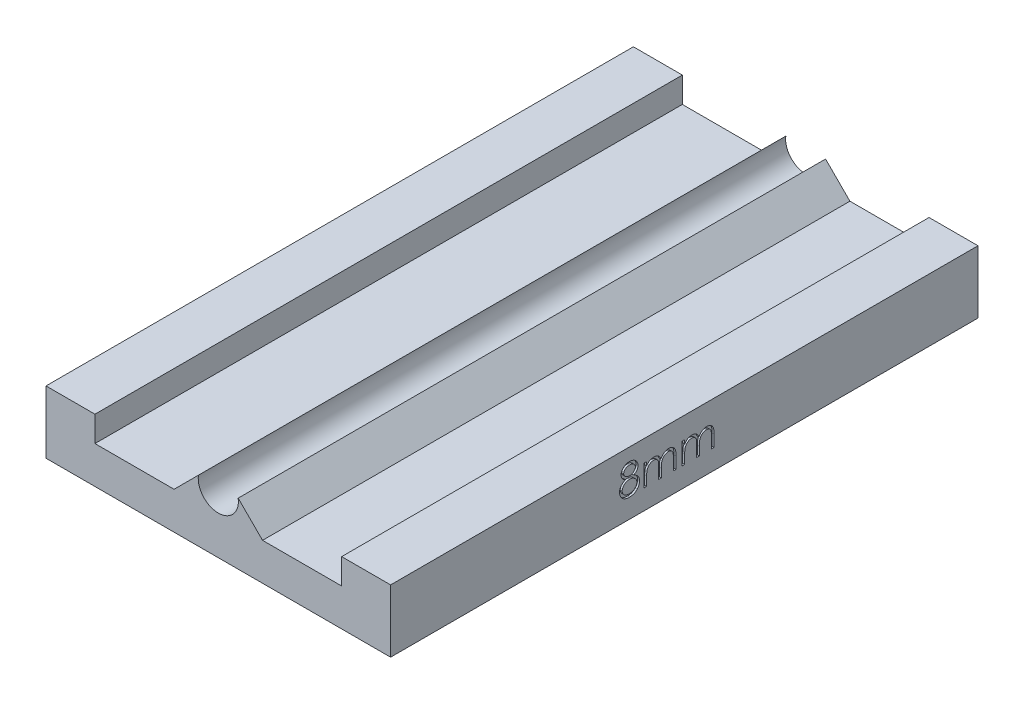
SolidWorks part; units mm, degrees
ref_plane "Front Plane" through (0, 0, 0) normal (0, 0, 1) x (1, 0, 0)
ref_plane "Top Plane" through (0, 0, 0) normal (0, 1, 0) x (1, 0, 0)
ref_plane "Right Plane" through (0, 0, 0) normal (1, 0, 0) x (0, 0, -1)
sketch "Sketch1" plane through (0, 0, 0) normal (0, 0, 1) x (1, 0, 0)
  line L0 (0, 0) -> (0, 5.7983) construction
  line L1 (0, 5.7983) -> (-10, -4.2017)
  line L2 (0, 5.7983) -> (10, -4.2017)
  line L3 (-10, -4.2017) -> (-25, -4.2017)
  line L4 (-25, -4.2017) -> (-25, 15.7983)
  line L5 (-25, 15.7983) -> (25, 15.7983)
  line L6 (25, 15.7983) -> (25, -4.2017)
  line L7 (25, -4.2017) -> (10, -4.2017)
  line L8 (-35.2, 0.7983) -> (-35.2, -12)
  line L9 (-35.2, -12) -> (35.2, -12)
  line L10 (35.2, -12) -> (35.2, 0.7983)
  line L11 (35.2, 0.7983) -> (25.2, 0.7983)
  line L12 (25.2, 0.7983) -> (25.2, -4.4017)
  line L13 (-25.2, -4.4017) -> (-9.0367, -4.4017)
  line L14 (-35.2, 0.7983) -> (-25.2, 0.7983)
  line L15 (-25.2, 0.7983) -> (-25.2, -4.4017)
  line L16 (25.2, -4.4017) -> (9.0367, -4.4017)
  line L17 (-9.0367, -4.4017) -> (-4.0594, 0.5755)
  line L18 (9.0367, -4.4017) -> (4.0594, 0.5755)
  circle A0 centre (0, 0) radius 4.1
  dimension "D12" = 8.2
  dimension "D1" = 45
  dimension "D2" = 10
  dimension "D3" = 20
  dimension "D4" = 50
  dimension "D5" = 25
  dimension "D6" = 5
  dimension "D7" = 0.2
  dimension "D8" = 0.2
  dimension "D9" = 5
  dimension "D10" = 10
  dimension "D11" = 10
  dimension "D13" = 12
  dimension "D14" = 0.2
  dimension "D15" = 0.2
extrude "Boss-Extrude1" add sketch "Sketch1" along normal blind 120 contours A0 L17 L13 L15 L14 L8 L9 L10 L11 L12 L16 L18
sketch "Sketch2" plane through (35.2, 0, 0) normal (1, 0, 0) x (0, 0, -1)
  text T0 "8mm" font "Century Gothic" height 6
extrude "Cut-Extrude1" cut sketch "Sketch2" against normal blind 0.4
